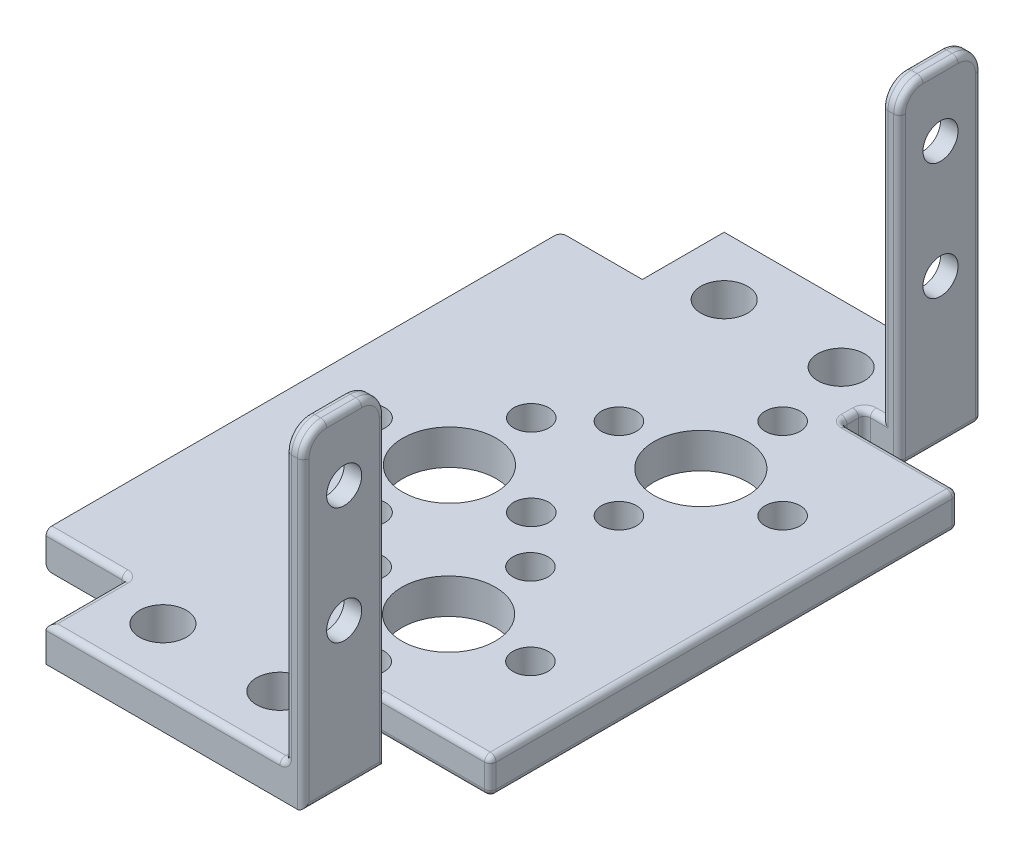
SolidWorks part; units mm, degrees
ref_plane "Front Plane" through (0, 0, 0) normal (0, 0, 1) x (1, 0, 0)
ref_plane "Top Plane" through (0, 0, 0) normal (0, 1, 0) x (1, 0, 0)
ref_plane "Right Plane" through (0, 0, 0) normal (1, 0, 0) x (0, 0, -1)
sketch "Sketch1" plane through (0, 0, 0) normal (0, 1, 0) x (1, 0, 0)
  line L1 (-18, 29) -> (18, 29)
  line L2 (-18, 29) -> (-18, -29)
  line L3 (-18, -29) -> (18, -29)
  line L4 (18, 29) -> (18, -29)
  line L5 (-18, 29) -> (18, -29) construction
  line L6 (-18, -29) -> (18, 29) construction
  line L7 (-18, 29) -> (-11, 29)
  line L8 (-18, 29) -> (-18, 22)
  line L9 (-18, 22) -> (-11, 22)
  line L10 (-11, 29) -> (-11, 22)
  line L11 (-11, -29) -> (-11, -22)
  line L12 (-18, -22) -> (-11, -22)
  line L13 (-18, -29) -> (-18, -22)
  line L14 (-18, -29) -> (-11, -29)
  line L24 (18, 29) -> (18, -29)
  line L26 (11, -22) -> (8, -22)
  line L27 (18, -22) -> (18, -20)
  line L28 (18, -20) -> (8, -20)
  line L29 (8, -22) -> (8, -20)
  line L33 (11, 29) -> (11, 22)
  line L34 (18, -29) -> (11, -29)
  line L35 (18, -29) -> (18, -22)
  line L37 (11, -29) -> (11, -22)
  line L38 (11, 22) -> (8, 22)
  line L39 (8, 22) -> (8, 20)
  line L40 (18, 20) -> (8, 20)
  point P0 (0, 0)
  dimension "D1" = 36
  dimension "D2" = 58
  dimension "D3" = 7
  dimension "D4" = 7
  dimension "D5" = 2
  dimension "D6" = 10
extrude "Boss-Extrude1" add sketch "Sketch1" along normal blind 3
sketch "Sketch3" plane through (0, 3, 0) normal (0, 1, 0) x (1, 0, 0)
  line L0 (11, 22) -> (8, 22) construction
  line L1 (11, 29) -> (9.5, 29)
  line L2 (11, 29) -> (11, 22)
  line L3 (11, 22) -> (9.5, 22)
  line L4 (9.5, 29) -> (9.5, 22)
  line L5 (11, -22) -> (8, -22) construction
  line L6 (11, -29) -> (9.5, -29)
  line L7 (11, -29) -> (11, -22)
  line L8 (11, -22) -> (9.5, -22)
  line L9 (9.5, -29) -> (9.5, -22)
extrude "Boss-Extrude2" add sketch "Sketch3" along normal blind 25
fillet "Fillet3" radius 2 4 edges at (10.25, 28, -29) (10.25, 28, -22) (10.25, 28, 29) (10.25, 28, 22)
fillet "Fillet4" radius 0.5 50 edges at (13, 3, -20) (-14.5, 3, 22) (-0.75, 3, 29) (11, 27.4142, -22.5858) (11, 28, -25.5) (11, 27.4142, -28.4142) (9.5, 27.4142, -28.4142) (9.5, 28, -25.5) (9.5, 27.4142, -22.5858) (11, 27.4142, 28.4142) (11, 28, 25.5) (11, 27.4142, 22.5858) (9.5, 27.4142, 28.4142) (9.5, 28, 25.5) (9.5, 27.4142, 22.5858) (11, 0, 25.5) (18, 1.5, -20) (8, 1.5, -20) (8, 1.5, -22) (11, 13, -22) (11, 13, -29) (-18, 1.5, -22) (8.75, 3, -22) (8, 3, -21) (-14.5, 0, -22) (-11, 0, -25.5) (0, 0, -29) (11, 0, -25.5) (9.5, 0, -22) (8, 0, -21) (13, 0, -20) (9.5, 14.5, -29) (9.5, 14.5, -22) (-11, 1.5, 22) (11, 13, 29) (11, 13, 22) (8.75, 3, 22) (-11, 3, 25.5) (9.5, 14.5, 29) (9.5, 14.5, 22) (9.5, 3, 25.5) (8, 1.5, 20) (18, 1.5, 20) (13, 3, 20) (8, 3, 21) (13, 0, 20) (8, 0, 21) (18, 0, 0) (-18, 0, 0) (18, 3, 0)
hole_wizard "Ø8.0mm Dowel Hole1" positions "Sketch6" profile "Sketch5" hole size "Ø8.0" standard "ISO" end condition through all
sketch "Sketch6" plane through (0, 0, 0) normal (0, -1, 0) x (-1, 0, 0)
  line L0 (-17.5, 19.5) -> (-17.5, -19.5) construction
  line L1 (10.5, 28.5) -> (-10.5, 28.5) construction
  line L2 (17.5, -22) -> (17.5, 21.5) construction
  line L3 (-10.5, 29) -> (11, 29) construction
  point P0 (-5.5, -11.0704)
  point P2 (-5.5, 10.5)
  point P4 (5.5, 0)
  dimension "D1" = 12
  dimension "D2" = 18
  dimension "D3" = 12
  dimension "D4" = 29
sketch "Sketch5" plane through (5.5, 0, 11.0704) normal (1, 0, 0) x (0, 0, -1)
  line L0 (0, 0) -> (0, 28)
  line L1 (0, 28) -> (4, 28)
  line L2 (4, 28) -> (4, 0)
  line L5 (4, 0) -> (0, 0)
  line L11 (0, -6.35) -> (0, 107.95) construction
  dimension "Thru Hole Dia." = 8
  dimension "Thru Hole Depth" = 28
hole_wizard "Ø3.0mm Dowel Hole1" positions "Sketch7" profile "Sketch8" hole size "Ø3.0" standard "ISO" end condition through all
sketch "Sketch7" plane through (0, 0, 0) normal (0, -1, 0) x (-1, 0, 0)
  point P45 (5.5, 0)
  point P48 (5.5, -7)
  point P50 (-5.5, -11.0704)
  point P53 (-5.5, -4.0704)
  point P55 (-5.5, 3.5)
  point P58 (-5.5, 10.5)
  point P71 (-1.5, 0)
  point P72 (5.5, 7)
  point P73 (12.5, 0)
  point P74 (5.5, 0)
  point P84 (1.5, -11.0704)
  point P85 (-5.5, -18.0704)
  point P86 (-12.5, -11.0704)
  point P87 (-5.5, -11.0704)
  point P93 (-12.5, 10.5)
  point P94 (-5.5, 17.5)
  point P95 (1.5, 10.5)
  point P96 (-5.5, 10.5)
  dimension "D1" = 7
  dimension "D2" = 7
  dimension "D3" = 7
sketch "Sketch8" plane through (-5.5, 0, 0) normal (1, 0, 0) x (0, 0, -1)
  line L0 (0, 0) -> (0, 28)
  line L1 (0, 28) -> (1.5, 28)
  line L2 (1.5, 28) -> (1.5, 0)
  line L5 (1.5, 0) -> (0, 0)
  line L11 (0, -6.35) -> (0, 107.95) construction
  dimension "Thru Hole Dia." = 3
  dimension "Thru Hole Depth" = 28
hole_wizard "Ø4.0mm Dowel Hole1" positions "Sketch9" profile "Sketch10" hole size "Ø4.0" standard "ISO" end condition through all
sketch "Sketch9" plane through (0, 0, 0) normal (0, -1, 0) x (-1, 0, 0)
  line L3 (11, -29) -> (11, -22.5) construction
  line L4 (11, -29) -> (-10.5, -29) construction
  line L5 (-10.5, 29) -> (11, 29) construction
  point P0 (-4, -24)
  point P2 (6, -24)
  point P4 (-4, 24)
  point P6 (6, 24)
  dimension "D1" = 5
  dimension "D2" = 5
  dimension "D3" = 10
  dimension "D4" = 5
sketch "Sketch10" plane through (4, 0, 24) normal (1, 0, 0) x (0, 0, -1)
  line L0 (0, 0) -> (0, 28)
  line L1 (0, 28) -> (2, 28)
  line L2 (2, 28) -> (2, 0)
  line L5 (2, 0) -> (0, 0)
  line L11 (0, -6.35) -> (0, 107.95) construction
  dimension "Thru Hole Dia." = 4
  dimension "Thru Hole Depth" = 28
hole_wizard "Ø3.0mm Dowel Hole2" positions "Sketch11" profile "Sketch12" hole size "Ø3.0" standard "ISO" end condition through all
sketch "Sketch11" plane through (11, 0, 0) normal (1, 0, 0) x (0, 0, -1)
  line L3 (28.5, 0.5) -> (28.5, 26) construction
  line L4 (27, 27.5) -> (24, 27.5) construction
  line L6 (-28.5, 26) -> (-28.5, 0.5) construction
  point P0 (25.5, 22.5)
  point P2 (25.5, 12.5)
  point P4 (-25.5, 12.5)
  point P6 (-25.5, 22.5)
  dimension "D1" = 5
  dimension "D2" = 10
  dimension "D3" = 3
  dimension "D4" = 3
sketch "Sketch12" plane through (11, 22.5, -25.5) normal (0, 1, 0) x (0, 0, -1)
  line L0 (0, 0) -> (0, 29)
  line L1 (0, 29) -> (1.5, 29)
  line L2 (1.5, 29) -> (1.5, 0)
  line L5 (1.5, 0) -> (0, 0)
  line L11 (0, -6.35) -> (0, 107.95) construction
  dimension "Thru Hole Dia." = 3
  dimension "Thru Hole Depth" = 29
